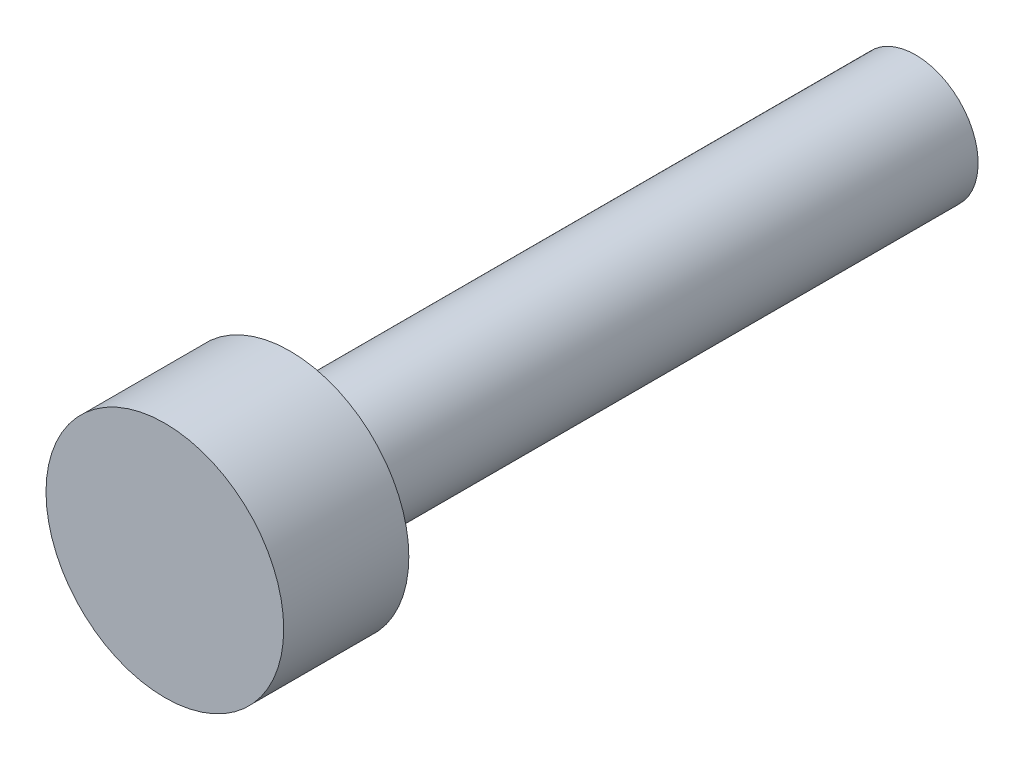
SolidWorks part; units mm, degrees
ref_plane "Front Plane" through (0, 0, 0) normal (0, 0, 1) x (1, 0, 0)
ref_plane "Top Plane" through (0, 0, 0) normal (0, 1, 0) x (1, 0, 0)
ref_plane "Right Plane" through (0, 0, 0) normal (1, 0, 0) x (0, 0, -1)
sketch "Sketch1" plane through (0, 0, 0) normal (0, 0, 1) x (1, 0, 0)
  circle A0 centre (0, 0) radius 3.8
  dimension "D1" = 7.6
extrude "Boss-Extrude1" add sketch "Sketch1" along normal blind 4
sketch "Sketch2" plane through (0, 0, 0) normal (0, 0, -1) x (-1, 0, 0)
  circle A0 centre (0, 0) radius 2
  dimension "D1" = 4
extrude "Boss-Extrude2" add sketch "Sketch2" along normal blind 20
